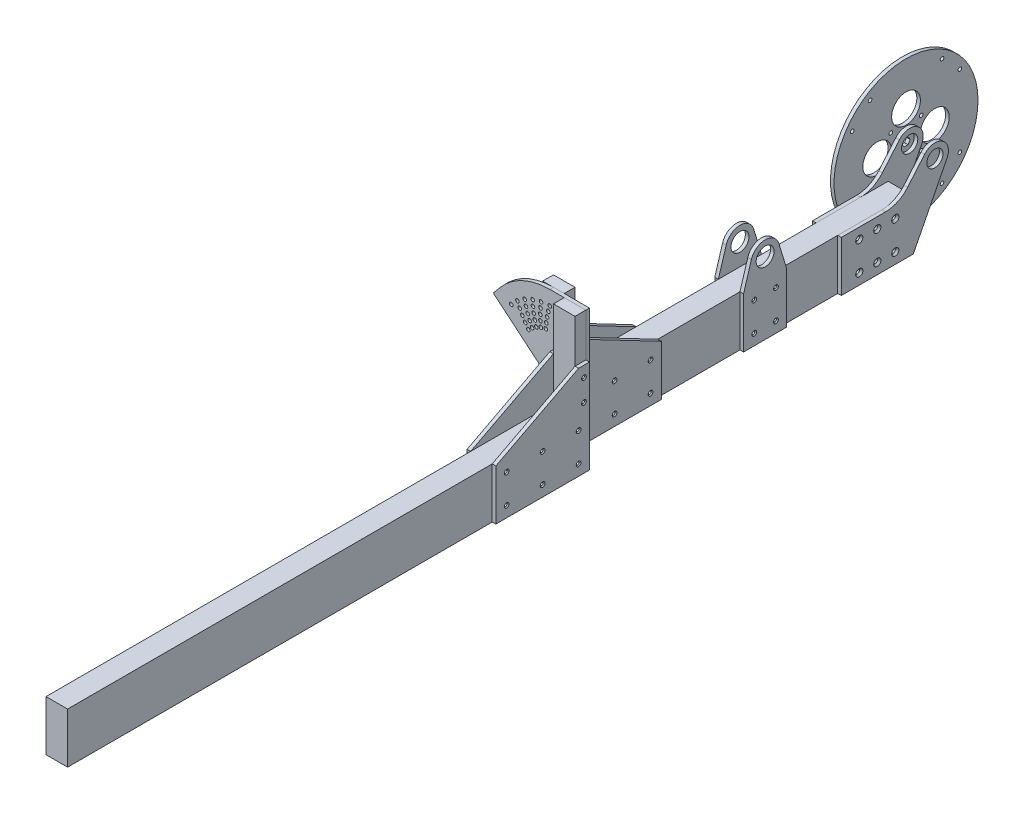
SolidWorks part; units mm, degrees
material "6061-T6 (SS)"
ref_plane "Front Plane" through (0, 0, 0) normal (0, 0, 1) x (1, 0, 0)
ref_plane "Top Plane" through (0, 0, 0) normal (0, 1, 0) x (1, 0, 0)
ref_plane "Right Plane" through (0, 0, 0) normal (1, 0, 0) x (0, 0, -1)
sketch "Sketch1" plane through (0, 0, 0) normal (1, 0, 0) x (0, 0, -1)
  line L1 (7.1857, 0) -> (3.5929, 6.223)
  line L2 (3.5929, 6.223) -> (-3.5929, 6.223)
  line L3 (-3.5929, 6.223) -> (-7.1857, 0)
  line L4 (-7.1857, 0) -> (-3.5929, -6.223)
  line L5 (-3.5929, -6.223) -> (3.5929, -6.223)
  line L6 (3.5929, -6.223) -> (7.1857, 0)
  circle A0 centre (0, 0) radius 127
  circle A2 centre (0, 50.8) radius 25.4
  circle A3 centre (50.8, 0) radius 25.4
  circle A4 centre (0, -50.8) radius 25.4
  circle A5 centre (-50.8, 0) radius 25.4
  circle A7 centre (0, 0) radius 203.2 construction
  circle A8 centre (0, 0) radius 6.223 construction
  point P6 (0, 0)
  point P14 (0, 0)
  dimension "D1" = 254
  dimension "D2" = 25.4
  dimension "D3" = 4
  dimension "2" = 50.8
  dimension "D4" = 12.446
  dimension "D5" = 406.4
extrude "Boss-Extrude1" add sketch "Sketch1" along normal blind 6.35
sketch "Sketch3" plane through (6.35, 0, 0) normal (1, 0, 0) x (0, 0, -1)
  line L0 (-26.9408, -26.9408) -> (26.9408, 26.9408) construction
  line L1 (-26.9408, 26.9408) -> (26.9408, -26.9408) construction
  line L2 (-63.5, 95.0381) -> (0, 0) construction
  line L3 (0, 0) -> (63.5, 95.0381) construction
  circle A0 centre (-26.9408, 26.9408) radius 3.175
  circle A1 centre (26.9408, 26.9408) radius 3.175
  circle A2 centre (26.9408, -26.9408) radius 3.175
  circle A3 centre (-26.9408, -26.9408) radius 3.175
  circle A4 centre (-63.5, 95.0381) radius 3.175
  circle A5 centre (63.5, 95.0381) radius 3.175
  circle A6 centre (95.0381, 63.5) radius 3.175
  circle A7 centre (95.0381, -63.5) radius 3.175
  circle A8 centre (63.5, -95.0381) radius 3.175
  circle A9 centre (-63.5, -95.0381) radius 3.175
  circle A10 centre (-95.0381, -63.5) radius 3.175
  circle A11 centre (-95.0381, 63.5) radius 3.175
  point P11 (-76.8833, 43.4257)
  point P13 (0, 0)
  point P29 (0, 0)
  dimension "D1" = 6.35
  dimension "D2" = 76.2
  dimension "D3" = 127
  dimension "D4" = 114.3
  dimension "D5" = 4
extrude "Cut-Extrude1" cut sketch "Sketch3" against normal blind 6.35
ref_plane "Plane1" through (6.477, 0, 0) normal (1, 0, 0) x (0, 0, -1)
sketch "Sketch4" plane through (6.477, 0, 0) normal (1, 0, 0) x (0, 0, -1)
  line L0 (-38.1, -127) -> (-165.1, -127)
  line L1 (-38.1, -38.1) -> (-235.8684, -38.1) construction
  line L2 (-38.1, -38.1) -> (-38.1, -127) construction
  line L3 (-38.1, -127) -> (-235.8684, -127) construction
  line L5 (-165.1, -127) -> (-165.1, -38.1)
  line L6 (-165.1, -38.1) -> (-87.038, -38.1)
  line L7 (-48.2824, -20.1427) -> (-18.1667, 15.395)
  line L8 (-38.1, -127) -> (21.2085, -10.8274)
  circle A0 centre (0, 0) radius 14.2875
  arc A1 (21.2085, -10.8274) -> (-18.1667, 15.395) centre (0, 0) ccw
  arc A2 (-87.038, -38.1) -> (-48.2824, -20.1427) centre (-87.038, 12.7) ccw
  point P11 (-189.7542, -38.1)
  point P15 (0, 0)
  point P16 (0, 0)
  point P18 (-63.5, -38.1)
  dimension "D1" = 28.575
  dimension "D5" = 9.525
  dimension "D8" = 50.8
  dimension "D2" = 127
  dimension "D3" = 38.1
  dimension "D4" = 38.1
  dimension "D6" = 101.6
  dimension "D7" = 88.9
extrude "Boss-Extrude2" add sketch "Sketch4" along normal blind 6.35 separate body
sketch "Sketch5" plane through (12.827, 0, 0) normal (1, 0, 0) x (0, 0, -1)
  line L0 (-133.35, -57.15) -> (-101.6, -57.15) construction
  line L1 (-101.6, -57.15) -> (-69.85, -57.15) construction
  line L2 (-69.85, -57.15) -> (-69.85, -107.95) construction
  line L3 (-69.85, -107.95) -> (-101.6, -107.95) construction
  line L4 (-101.6, -107.95) -> (-101.6, -57.15) construction
  line L5 (-101.6, -107.95) -> (-133.35, -107.95) construction
  line L6 (-133.35, -107.95) -> (-133.35, -57.15) construction
  line L7 (-133.35, -57.15) -> (-133.35, -38.1) construction
  line L8 (-87.038, -38.1) -> (-165.1, -38.1) construction
  line L9 (-133.35, -57.15) -> (-165.1, -57.15) construction
  line L10 (-165.1, -38.1) -> (-165.1, -127) construction
  line L11 (-69.85, -107.95) -> (-38.1, -107.95) construction
  line L12 (-69.85, -107.95) -> (-69.85, -127) construction
  line L13 (-165.1, -127) -> (-38.1, -127) construction
  circle A0 centre (-133.35, -57.15) radius 3.175
  circle A1 centre (-101.6, -57.15) radius 3.175
  circle A2 centre (-69.85, -57.15) radius 3.175
  circle A3 centre (-133.35, -107.95) radius 3.175
  circle A4 centre (-101.6, -107.95) radius 3.175
  circle A5 centre (-69.85, -107.95) radius 3.175
  point P19 (-133.35, -47.9124)
  point P21 (-69.85, -109.4142)
  dimension "D2" = 6.35
  dimension "D1" = 19.05
extrude "Cut-Extrude2" cut sketch "Sketch5" against normal blind 6.35
chamfer "Chamfer1" distance 3.175 angle 45 6 edges at (6.477, -107.95, 130.175) (6.477, -57.15, 130.175) (6.477, -107.95, 98.425) (6.477, -57.15, 98.425) (6.477, -107.95, 66.675) (6.477, -57.15, 66.675)
ref_plane "Plane2" through (0, 0, 38.1) normal (0, 0, 1) x (1, 0, 0)
sketch "Sketch7" plane through (0, 0, 38.1) normal (0, 0, 1) x (1, 0, 0)
  line L1 (12.827, -127) -> (50.927, -127)
  line L2 (12.827, -127) -> (12.827, -38.1)
  line L3 (12.827, -38.1) -> (50.927, -38.1)
  line L4 (50.927, -127) -> (50.927, -38.1)
  point P4 (0, 0)
  point P6 (12.827, -26.7292)
  point P7 (0, 0)
  point P8 (0, 0)
  dimension "D1" = 38.1
extrude "Boss-Extrude3" add sketch "Sketch7" along normal blind 609.6 separate body
ref_plane "Plane3" through (31.877, 0, 0) normal (1, 0, 0) x (0, 0, -1)
mirror "Mirror1" about plane through (31.877, 0, 0) normal (1, 0, 0) of bodies 104
sketch "Sketch8" plane through (0, -38.1, 0) normal (0, 1, 0) x (1, 0, 0)
  line L0 (12.827, -647.7) -> (12.827, -38.1) construction
  line L1 (50.927, -647.7) -> (12.827, -647.7)
  line L2 (50.927, -647.7) -> (50.927, -628.65)
  line L3 (50.927, -628.65) -> (12.827, -628.65)
  line L4 (12.827, -647.7) -> (12.827, -628.65)
  dimension "D1" = 19.05
extrude "Boss-Extrude4" add sketch "Sketch8" along normal blind 152.4 separate body
sketch "Sketch9" plane through (12.827, 0, 0) normal (-1, 0, 0) x (0, 0, 1)
  line L0 (647.7, 38.1) -> (647.7, -127)
  line L1 (647.7, 114.3) -> (647.7, -38.1) construction
  line L2 (647.7, -127) -> (482.6, -127)
  line L3 (482.6, -127) -> (482.6, -38.1)
  line L4 (647.7, -38.1) -> (38.1, -38.1) construction
  line L5 (482.6, -38.1) -> (628.65, 38.1)
  line L6 (628.65, 114.3) -> (628.65, -38.1) construction
  line L7 (628.65, 38.1) -> (647.7, 38.1)
extrude "Boss-Extrude5" add sketch "Sketch9" along normal blind 6.35 separate body
hole_wizard "CSK for #8 Flat Head Machine Screw (100)1" positions "Sketch12" profile "Sketch11" countersink size "#8" standard "ANSI Inch"
sketch "Sketch12" plane through (6.477, 0, 0) normal (-1, 0, 0) x (0, 0, 1)
  line L0 (638.175, -19.05) -> (638.175, 19.05) construction
  line L2 (628.65, 19.05) -> (647.7, 19.05) construction
  line L4 (647.7, 114.3) -> (647.7, -38.1) construction
  line L5 (628.65, 114.3) -> (628.65, -38.1) construction
  line L6 (638.175, 19.05) -> (638.175, 38.1) construction
  line L7 (647.7, 38.1) -> (628.65, 38.1) construction
  line L9 (628.65, -107.95) -> (628.65, -57.15) construction
  line L10 (628.65, -57.15) -> (565.15, -57.15) construction
  line L11 (565.15, -57.15) -> (501.65, -57.15) construction
  line L13 (565.15, -57.15) -> (565.15, -107.95) construction
  line L15 (501.65, -57.15) -> (501.65, -107.95) construction
  line L16 (501.65, -107.95) -> (565.15, -107.95) construction
  line L17 (565.15, -107.95) -> (628.65, -107.95) construction
  line L19 (647.7, -127) -> (647.7, 38.1) construction
  line L20 (482.6, -127) -> (647.7, -127) construction
  line L21 (628.65, -107.95) -> (628.65, -127) construction
  line L23 (628.65, -107.95) -> (647.7, -107.95) construction
  line L25 (501.65, -57.15) -> (501.65, -38.1) construction
  line L27 (647.7, -38.1) -> (38.1, -38.1) construction
  line L28 (501.65, -57.15) -> (482.6, -57.15) construction
  line L29 (482.6, -38.1) -> (482.6, -127) construction
  point P0 (638.175, 19.05)
  point P2 (638.175, -19.05)
  point P4 (628.65, -57.15)
  point P6 (628.65, -107.95)
  point P8 (565.15, -107.95)
  point P10 (565.15, -57.15)
  point P12 (501.65, -57.15)
  point P14 (501.65, -107.95)
  point P81 (0, 0)
  point P82 (1111.25, -44.45)
  dimension "D1" = 19.05
  dimension "D2" = 38.1
  dimension "D3" = 19.05
  dimension "D4" = 19.05
sketch "Sketch11" plane through (6.477, 19.05, 638.175) normal (0, 1, 0) x (0, 0, 1)
  line L0 (0, 0) -> (0, 8.9453)
  line L1 (0, 8.9453) -> (2.2479, 7.5946)
  line L2 (2.2479, 7.5946) -> (2.2479, 1.6518)
  line L3 (2.2479, 1.6518) -> (4.2164, 0)
  line L5 (4.2164, 0) -> (0, 0)
  line L6 (-2.2479, 1.6518) -> (-4.2164, 0) construction
  line L10 (0, 8.9453) -> (-2.2479, 7.5946) construction
  line L11 (0, -6.35) -> (0, 107.95) construction
  dimension "Hole Dia." = 4.4958
  dimension "Hole Depth" = 7.5946
  dimension "Near C'Sink Dia." = 8.4328
  dimension "Near C'Sink Angle" = 100
  dimension "Drill Angle" = 118
mirror "Mirror2" about plane through (31.877, 0, 0) normal (1, 0, 0) of bodies 111
sketch "Sketch13" plane through (0, 0, 647.7) normal (0, 0, 1) x (1, 0, 0)
  line L0 (12.827, 0) -> (50.927, 0) construction
  line L1 (12.827, 114.3) -> (12.827, -38.1) construction
  line L2 (50.927, -127) -> (50.927, 38.1) construction
  circle A0 centre (31.877, 0) radius 3.175
  circle A1 centre (31.877, 88.9) radius 3.175
  point P2 (0, 0)
  point P12 (0, 0)
  dimension "D1" = 6.35
  dimension "D2" = 88.9
extrude "Cut-Extrude3" cut sketch "Sketch13" against normal up to next (19.05 mm away)
sketch "Sketch16" plane through (0, 0, 647.7) normal (0, 0, 1) x (1, 0, 0)
  line L0 (31.877, 88.9) -> (31.877, 79.375) construction
  line L1 (31.877, 79.375) -> (31.877, 69.85) construction
  line L2 (31.877, 69.85) -> (31.877, 60.325) construction
  line L3 (31.877, 60.325) -> (31.877, 50.8) construction
  circle A0 centre (31.877, 79.375) radius 3.175
  circle A1 centre (31.877, 69.85) radius 3.175
  circle A2 centre (31.877, 60.325) radius 3.175
  circle A3 centre (31.877, 50.8) radius 3.175
  circle A5 centre (31.877, 88.9) radius 3.175 construction
  point P12 (35.1533, 79.375)
  dimension "D1" = 9.525
extrude "Cut-Extrude5" cut sketch "Sketch16" against normal up to next (19.05 mm away)
sketch "Sketch14" plane through (0, 0, 647.7) normal (0, 0, 1) x (1, 0, 0)
  line L1 (57.277, -38.1) -> (12.827, -38.1)
  line L2 (12.827, 114.3) -> (50.927, 114.3) construction
  line L3 (-55.6819, 73.4706) -> (31.877, 0) construction
  line L4 (31.877, 79.375) -> (31.877, 0) construction
  line L5 (31.877, 0) -> (29.1069, 79.3266) construction
  line L6 (31.877, 0) -> (29.1069, 79.3266) construction
  line L7 (31.877, 0) -> (15.374, 77.6405) construction
  line L8 (31.877, 0) -> (27.0045, 69.6798) construction
  line L9 (31.877, 69.85) -> (31.877, 0) construction
  line L10 (-21.2352, 58.9871) -> (31.877, 0) construction
  line L11 (25.5713, 59.9945) -> (31.877, 0) construction
  line L12 (31.877, 60.325) -> (31.877, 0) construction
  line L13 (24.807, 50.3056) -> (31.877, 0) construction
  line L14 (31.877, 0) -> (31.877, 50.8) construction
  line L15 (31.877, 0) -> (27.0045, 69.6798) construction
  line L16 (31.877, 0) -> (14.9788, 67.7752) construction
  line L17 (31.877, 0) -> (25.5713, 59.9945) construction
  line L18 (31.877, 0) -> (15.2492, 57.9881) construction
  line L19 (31.877, 0) -> (24.807, 50.3056) construction
  line L20 (31.877, 0) -> (16.1789, 48.3137) construction
  line L21 (31.877, 0) -> (31.877, 88.9) construction
  line L22 (31.877, 0) -> (16.4397, 87.5494) construction
  line L23 (12.827, -127) -> (12.827, 38.1) construction
  line L24 (12.827, 114.3) -> (12.827, -38.1) construction
  line L25 (31.877, 114.3) -> (50.927, 114.3)
  line L26 (-55.6819, 73.4706) -> (-67.927, 58.8775)
  line L27 (-67.927, 58.8775) -> (12.827, -8.8832)
  line L28 (12.827, -8.8832) -> (12.827, -38.1)
  line L30 (95.377, 114.3) -> (95.377, -38.1)
  line L33 (57.277, -127) -> (57.277, 38.1) construction
  line L34 (50.927, -38.1) -> (12.827, -38.1) construction
  line L35 (57.277, -38.1) -> (95.377, -38.1)
  line L37 (95.377, 114.3) -> (50.927, 114.3)
  line L39 (50.927, 114.3) -> (12.827, 114.3) construction
  line L40 (50.927, 114.3) -> (50.927, -38.1) construction
  arc A0 (31.877, 114.3) -> (-55.6819, 73.4706) centre (31.877, 0) ccw
  circle A1 centre (31.877, 0) radius 3.175 construction
  circle A2 centre (31.877, 88.9) radius 3.175
  circle A3 centre (31.877, 88.9) radius 3.175 construction
  circle A8 centre (29.1069, 79.3266) radius 3.175
  circle A9 centre (31.877, 79.375) radius 3.175 construction
  circle A10 centre (15.374, 77.6405) radius 3.175
  circle A11 centre (2.1426, 73.5952) radius 3.175
  circle A12 centre (-10.1853, 67.3138) radius 3.175
  circle A13 centre (-21.2352, 58.9871) radius 3.175
  circle A14 centre (27.0045, 69.6798) radius 3.175
  circle A15 centre (25.5713, 59.9945) radius 3.175
  circle A16 centre (24.807, 50.3056) radius 3.175
  circle A17 centre (31.877, 69.85) radius 3.175 construction
  circle A18 centre (14.9788, 67.7752) radius 3.175
  circle A19 centre (3.4664, 63.8112) radius 3.175
  circle A20 centre (-7.1826, 57.9083) radius 3.175
  circle A21 centre (-16.6449, 50.2459) radius 3.175
  circle A22 centre (15.2492, 57.9881) radius 3.175
  circle A23 centre (5.4323, 54.2198) radius 3.175
  circle A24 centre (-3.5811, 48.804) radius 3.175
  circle A25 centre (-11.5172, 41.9053) radius 3.175
  circle A26 centre (16.1789, 48.3137) radius 3.175
  circle A27 centre (8.0278, 44.8537) radius 3.175
  circle A28 centre (0.6014, 40.0309) radius 3.175
  circle A29 centre (-5.8748, 33.9918) radius 3.175
  circle A30 centre (16.4397, 87.5494) radius 3.175
  circle A31 centre (1.4714, 83.5387) radius 3.175
  circle A32 centre (-12.573, 76.9897) radius 3.175
  circle A33 centre (-25.2668, 68.1014) radius 3.175
  circle A34 centre (-36.2244, 57.1438) radius 3.175
  circle A35 centre (31.877, 0) radius 3.175
  point P2 (-66.5577, 58.9871)
  point P28 (31.877, 0)
  point P95 (0, 0)
  dimension "D3" = 2
  dimension "D5" = 10
  dimension "D6" = 4
  dimension "D7" = 6
  dimension "D8" = 8
  dimension "D10" = 10
  dimension "D12" = 10
  dimension "D14" = 10
  dimension "D15" = 10
  dimension "D4" = 5
  dimension "D9" = 5
  dimension "D11" = 5
  dimension "D13" = 5
  dimension "D2" = 6
extrude "Boss-Extrude6" add sketch "Sketch14" along normal blind 6.35 separate body
hole_wizard "CSK for #8 Flat Head Machine Screw (100)2" positions "Sketch19" profile "Sketch20" countersink size "#8" standard "ANSI Inch"
sketch "Sketch19" plane through (0, 0, 647.7) normal (0, 0, -1) x (-1, 0, 0)
  line L0 (-95.377, -12.7) -> (-57.277, -12.7) construction
  line L1 (-95.377, -38.1) -> (-95.377, 114.3) construction
  line L2 (-57.277, -127) -> (-57.277, 38.1) construction
  line L4 (-76.327, -12.7) -> (-76.327, -38.1) construction
  line L5 (-12.827, -38.1) -> (-95.377, -38.1) construction
  line L7 (-76.327, -12.7) -> (-76.327, 12.7) construction
  line L8 (-76.327, 12.7) -> (-76.327, 38.1) construction
  line L9 (-76.327, 38.1) -> (-76.327, 63.5) construction
  line L10 (-76.327, 63.5) -> (-76.327, 88.9) construction
  line L11 (-76.327, 88.9) -> (-76.327, 114.3) construction
  line L12 (-95.377, 114.3) -> (-31.877, 114.3) construction
  point P9 (-76.327, -12.7)
  point P16 (-76.327, 12.7)
  point P17 (-76.327, 38.1)
  point P19 (-76.327, 63.5)
  point P21 (-76.327, 88.9)
sketch "Sketch20" plane through (76.327, 88.9, 647.7) normal (1, 0, 0) x (0, 1, 0)
  line L0 (0, 0) -> (0, 7.7007)
  line L1 (0, 7.7007) -> (2.2479, 6.35)
  line L2 (2.2479, 6.35) -> (2.2479, 1.6518)
  line L3 (2.2479, 1.6518) -> (4.2164, 0)
  line L5 (4.2164, 0) -> (0, 0)
  line L6 (-2.2479, 1.6518) -> (-4.2164, 0) construction
  line L10 (0, 7.7007) -> (-2.2479, 6.35) construction
  line L11 (0, -6.35) -> (0, 107.95) construction
  dimension "Hole Dia." = 4.4958
  dimension "Hole Depth" = 6.35
  dimension "Near C'Sink Dia." = 8.4328
  dimension "Near C'Sink Angle" = 100
  dimension "Drill Angle" = 118
sketch "Sketch21" plane through (0, 0, 654.05) normal (0, 0, 1) x (1, 0, 0)
  line L0 (12.827, -38.1) -> (95.377, -38.1) construction
  line L1 (95.377, 114.3) -> (57.277, 114.3)
  line L2 (95.377, 114.3) -> (95.377, -38.1)
  line L3 (95.377, -38.1) -> (57.277, -38.1)
  line L4 (57.277, 114.3) -> (57.277, -38.1)
  line L5 (12.827, -127) -> (50.927, -127) construction
extrude "Boss-Extrude7" add sketch "Sketch21" along normal blind 19.05 separate body
ref_plane "Plane4" through (0, 0, 650.875) normal (0, 0, 1) x (1, 0, 0)
sketch "Sketch23" plane through (31.877, 0, 0) normal (1, 0, 0) x (0, 0, -1)
  line L0 (-302.7297, 25.1936) -> (-8.078, 62.9841)
  line L1 (-302.7297, -25.1936) -> (-8.078, -62.9841)
  circle A0 centre (0, 0) radius 63.5 construction
  circle A1 centre (-299.4985, 0) radius 25.4 construction
  arc A2 (-302.7297, 25.1936) -> (-302.7297, -25.1936) centre (-299.4985, 0) ccw
  arc A3 (-8.078, 62.9841) -> (-8.078, -62.9841) centre (0, 0) cw
  dimension "D1" = 127
  dimension "D2" = 50.8
  dimension "D3" = 883.138
sketch "Sketch24" plane through (50.927, 0, 0) normal (1, 0, 0) x (0, 0, -1)
  line L0 (-337.5985, -127) -> (-261.3985, -127)
  line L1 (-647.7, -127) -> (-38.1, -127) construction
  line L2 (-337.5985, -127) -> (-337.5985, -38.1)
  line L3 (-647.7, -38.1) -> (-38.1, -38.1) construction
  line L4 (-337.5985, -38.1) -> (-323.8049, 7.373)
  line L5 (-275.1922, 7.373) -> (-261.3985, -38.1)
  line L6 (-261.3985, -38.1) -> (-261.3985, -127)
  circle A0 centre (-299.4985, 0) radius 15.875
  arc A2 (-302.7297, 25.1936) -> (-302.7297, -25.1936) centre (-299.4985, 0) ccw construction
  circle A3 centre (-299.4985, 0) radius 25.4 construction
  arc A4 (-323.8049, 7.373) -> (-275.1922, 7.373) centre (-299.4985, 0) cw
  point P16 (-299.4985, -127)
  point P17 (-323.6114, -7.9831)
  dimension "D1" = 31.75
  dimension "D2" = 9.525
  dimension "D3" = 76.2
extrude "Boss-Extrude11" add sketch "Sketch24" along normal blind 6.35 separate body
hole_wizard "CSK for #8 Flat Head Machine Screw (100)3" positions "Sketch25" profile "Sketch26" countersink size "#8" standard "ANSI Inch"
sketch "Sketch25" plane through (57.277, 0, 0) normal (1, 0, 0) x (0, 0, -1)
  line L0 (-318.5485, -57.15) -> (-318.5485, -107.95) construction
  line L1 (-318.5485, -107.95) -> (-280.4485, -107.95) construction
  line L3 (-318.5485, -107.95) -> (-318.5485, -127) construction
  line L4 (-337.5985, -127) -> (-261.3985, -127) construction
  line L6 (-318.5485, -107.95) -> (-337.5985, -107.95) construction
  line L7 (-337.5985, -38.1) -> (-337.5985, -127) construction
  line L9 (-280.4485, -57.15) -> (-280.4485, -38.1) construction
  line L11 (-280.4485, -57.15) -> (-261.3985, -57.15) construction
  line L12 (-261.3985, -127) -> (-261.3985, -38.1) construction
  line L14 (-647.7, -38.1) -> (-38.1, -38.1) construction
  point P0 (-280.4485, -57.15)
  point P2 (-280.4485, -107.95)
  point P4 (-318.5485, -107.95)
  point P6 (-318.5485, -57.15)
  point P37 (0, 0)
  dimension "D1" = 19.05
sketch "Sketch26" plane through (57.277, -57.15, 280.4485) normal (0, 1, 0) x (0, 0, -1)
  line L0 (0, 0) -> (0, 7.7007)
  line L1 (0, 7.7007) -> (2.2479, 6.35)
  line L2 (2.2479, 6.35) -> (2.2479, 1.6518)
  line L3 (2.2479, 1.6518) -> (4.2164, 0)
  line L5 (4.2164, 0) -> (0, 0)
  line L6 (-2.2479, 1.6518) -> (-4.2164, 0) construction
  line L10 (0, 7.7007) -> (-2.2479, 6.35) construction
  line L11 (0, -6.35) -> (0, 107.95) construction
  dimension "Hole Dia." = 4.4958
  dimension "Hole Depth" = 6.35
  dimension "Near C'Sink Dia." = 8.4328
  dimension "Near C'Sink Angle" = 100
  dimension "Drill Angle" = 118
mirror "Mirror4" about plane through (31.877, 0, 0) normal (1, 0, 0) of bodies 124
sketch "Sketch27" plane through (57.277, 0, 0) normal (-1, 0, 0) x (0, 0, 1)
  line L0 (654.05, 38.1) -> (654.05, -127)
  line L1 (654.05, 114.3) -> (654.05, -38.1) construction
  line L2 (654.05, -127) -> (819.15, -127)
  line L3 (819.15, -127) -> (819.15, -38.1)
  line L4 (819.15, -38.1) -> (673.1, 38.1)
  line L5 (673.1, 114.3) -> (673.1, -38.1) construction
  line L6 (673.1, 38.1) -> (654.05, 38.1)
  line L7 (647.7, 38.1) -> (628.65, 38.1) construction
  line L8 (482.6, -127) -> (647.7, -127) construction
  line L9 (647.7, -38.1) -> (38.1, -38.1) construction
  point P13 (0, 0)
  point P16 (764.2547, -38.1)
  point P17 (812.7953, -38.1)
extrude "Boss-Extrude12" add sketch "Sketch27" along normal blind 6.35 separate body
hole_wizard "CSK for #8 Flat Head Machine Screw (100)4" positions "Sketch29" profile "Sketch30" countersink size "#8" standard "ANSI Inch"
sketch "Sketch29" plane through (50.927, 0, 0) normal (-1, 0, 0) x (0, 0, 1)
  line L0 (654.05, 19.05) -> (673.1, 19.05) construction
  line L1 (654.05, 38.1) -> (654.05, -127) construction
  line L3 (673.1, 114.3) -> (673.1, -38.1) construction
  line L4 (673.1, 38.1) -> (654.05, 38.1) construction
  line L5 (673.1, -107.95) -> (673.1, -127) construction
  line L6 (654.05, -127) -> (819.15, -127) construction
  line L8 (673.1, -107.95) -> (654.05, -107.95) construction
  line L10 (800.1, -57.15) -> (819.15, -57.15) construction
  line L11 (819.15, -127) -> (819.15, -38.1) construction
  line L13 (800.1, -57.15) -> (800.1, -38.1) construction
  line L15 (673.1, -107.95) -> (736.6, -107.95) construction
  line L16 (736.6, -107.95) -> (800.1, -107.95) construction
  point P0 (663.575, 19.05)
  point P2 (663.575, -19.05)
  point P4 (673.1, -57.15)
  point P6 (673.1, -107.95)
  point P8 (736.6, -57.15)
  point P10 (736.6, -107.95)
  point P12 (800.1, -57.15)
  point P14 (800.1, -107.95)
  point P65 (0, 0)
  dimension "D1" = 19.05
  dimension "D2" = 38.1
  dimension "D3" = 19.05
sketch "Sketch30" plane through (50.927, 19.05, 663.575) normal (0, 1, 0) x (0, 0, 1)
  line L0 (0, 0) -> (0, 7.7007)
  line L1 (0, 7.7007) -> (2.2479, 6.35)
  line L2 (2.2479, 6.35) -> (2.2479, 1.6518)
  line L3 (2.2479, 1.6518) -> (4.2164, 0)
  line L5 (4.2164, 0) -> (0, 0)
  line L6 (-2.2479, 1.6518) -> (-4.2164, 0) construction
  line L10 (0, 7.7007) -> (-2.2479, 6.35) construction
  line L11 (0, -6.35) -> (0, 107.95) construction
  dimension "Hole Dia." = 4.4958
  dimension "Hole Depth" = 6.35
  dimension "Near C'Sink Dia." = 8.4328
  dimension "Near C'Sink Angle" = 100
  dimension "Drill Angle" = 118
sketch "Sketch33" plane through (0, 0, 654.05) normal (0, 0, 1) x (1, 0, 0)
  line L1 (57.277, -38.1) -> (95.377, -38.1)
  line L2 (57.277, -38.1) -> (57.277, -127)
  line L3 (57.277, -127) -> (95.377, -127)
  line L4 (95.377, -38.1) -> (95.377, -127)
  point P4 (0, 0)
  dimension "D1" = 38.1
  dimension "D2" = 88.9
extrude "Boss-Extrude13" add sketch "Sketch33" along normal blind 914.4 separate body
ref_plane "Plane5" through (76.327, 0, 0) normal (1, 0, 0) x (0, 0, -1)
mirror "Mirror5" about plane through (76.327, 0, 0) normal (1, 0, 0) of bodies 128
